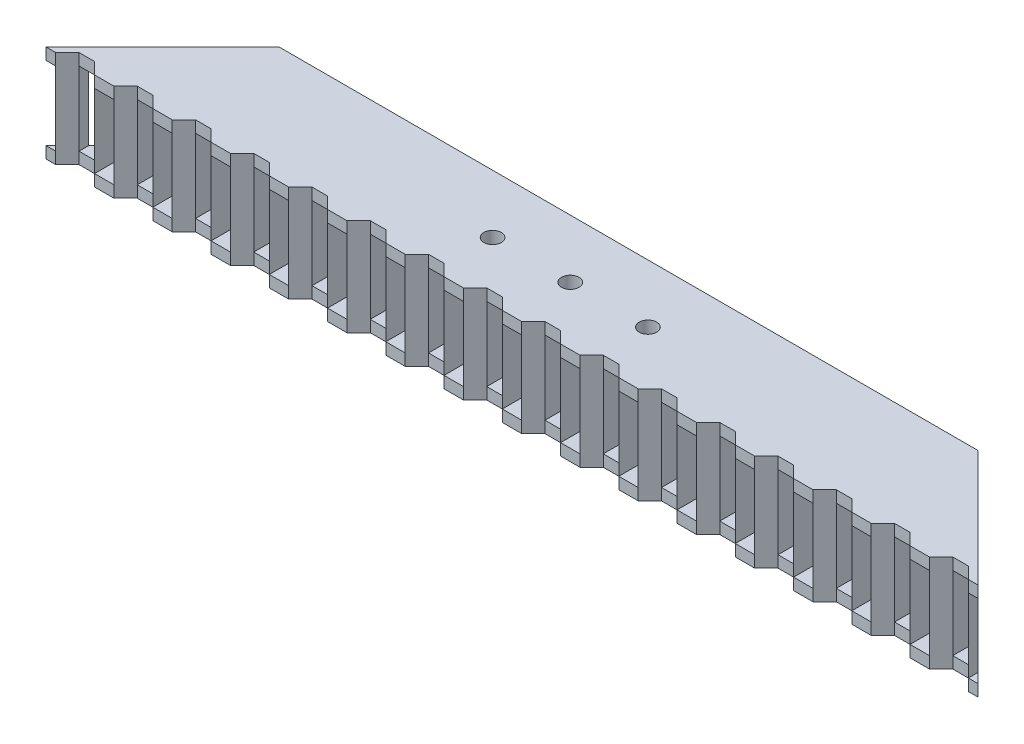
SolidWorks part; units mm, degrees
ref_plane "Front Plane" through (0, 0, 0) normal (0, 0, 1) x (1, 0, 0)
ref_plane "Top Plane" through (0, 0, 0) normal (0, 1, 0) x (1, 0, 0)
ref_plane "Right Plane" through (0, 0, 0) normal (1, 0, 0) x (0, 0, -1)
sketch "Sketch1" plane through (0, 0, 0) normal (0, 1, 0) x (1, 0, 0)
  line L0 (0, 0) -> (-120, 0)
  line L1 (0, 0) -> (120, 0)
  line L2 (120, 0) -> (90, 30)
  line L3 (90, 30) -> (-90, 30)
  line L4 (-90, 30) -> (-120, 0)
  line L5 (-105, 15) -> (0, 15) construction
  line L6 (0, 15) -> (0, 30) construction
  circle A0 centre (0, 15) radius 2.25
  circle A1 centre (-20, 15) radius 2.25
  circle A2 centre (20, 15) radius 2.25
  dimension "D6" = 4.5
  dimension "D1" = 45
  dimension "D2" = 45
  dimension "D3" = 30
  dimension "D4" = 120
  dimension "D5" = 120
  dimension "D7" = 20
  dimension "D8" = 20
extrude "Boss-Extrude1" add sketch "Sketch1" along normal blind 25
sketch "Sketch2" plane through (0, 25, 0) normal (0, 1, 0) x (1, 0, 0)
  line L0 (0, 0) -> (2.5, 0)
  line L1 (-120, 0) -> (120, 0) construction
  line L2 (2.5, 0) -> (5.5, 3)
  line L3 (5.5, 3) -> (9.5, 3)
  line L4 (9.5, 3) -> (12.5, 0)
  line L5 (0, 0) -> (-2.5, 0)
  line L6 (15, 0) -> (12.5, 0)
  line L7 (15, 0) -> (17.5, 0)
  line L8 (17.5, 0) -> (20.5, 3)
  line L9 (20.5, 3) -> (24.5, 3)
  line L10 (24.5, 3) -> (27.5, 0)
  line L11 (30, 0) -> (27.5, 0)
  line L12 (30, 0) -> (32.5, 0)
  line L13 (32.5, 0) -> (35.5, 3)
  line L14 (35.5, 3) -> (39.5, 3)
  line L15 (39.5, 3) -> (42.5, 0)
  line L16 (45, 0) -> (42.5, 0)
  line L17 (45, 0) -> (47.5, 0)
  line L18 (47.5, 0) -> (50.5, 3)
  line L19 (50.5, 3) -> (54.5, 3)
  line L20 (54.5, 3) -> (57.5, 0)
  line L21 (60, 0) -> (57.5, 0)
  line L22 (60, 0) -> (62.5, 0)
  line L23 (62.5, 0) -> (65.5, 3)
  line L24 (65.5, 3) -> (69.5, 3)
  line L25 (69.5, 3) -> (72.5, 0)
  line L26 (75, 0) -> (72.5, 0)
  line L27 (75, 0) -> (77.5, 0)
  line L28 (77.5, 0) -> (80.5, 3)
  line L29 (80.5, 3) -> (84.5, 3)
  line L30 (84.5, 3) -> (87.5, 0)
  line L31 (90, 0) -> (87.5, 0)
  line L32 (90, 0) -> (92.5, 0)
  line L33 (92.5, 0) -> (95.5, 3)
  line L34 (95.5, 3) -> (99.5, 3)
  line L35 (99.5, 3) -> (102.5, 0)
  line L36 (105, 0) -> (102.5, 0)
  line L37 (105, 0) -> (107.5, 0)
  line L38 (107.5, 0) -> (110.5, 3)
  line L39 (110.5, 3) -> (114.5, 3)
  line L40 (114.5, 3) -> (117.5, 0)
  line L41 (120, 0) -> (117.5, 0)
  line L42 (120, 0) -> (122.5, 0)
  line L43 (122.5, 0) -> (125.5, 3)
  line L44 (125.5, 3) -> (129.5, 3)
  line L45 (129.5, 3) -> (132.5, 0)
  line L46 (-15, 0) -> (-17.5, 0)
  line L47 (-15, 0) -> (-12.5, 0)
  line L48 (-12.5, 0) -> (-9.5, 3)
  line L49 (-9.5, 3) -> (-5.5, 3)
  line L50 (-5.5, 3) -> (-2.5, 0)
  line L51 (-30, 0) -> (-32.5, 0)
  line L52 (-30, 0) -> (-27.5, 0)
  line L53 (-27.5, 0) -> (-24.5, 3)
  line L54 (-24.5, 3) -> (-20.5, 3)
  line L55 (-20.5, 3) -> (-17.5, 0)
  line L56 (-45, 0) -> (-47.5, 0)
  line L57 (-45, 0) -> (-42.5, 0)
  line L58 (-42.5, 0) -> (-39.5, 3)
  line L59 (-39.5, 3) -> (-35.5, 3)
  line L60 (-35.5, 3) -> (-32.5, 0)
  line L61 (-60, 0) -> (-62.5, 0)
  line L62 (-60, 0) -> (-57.5, 0)
  line L63 (-57.5, 0) -> (-54.5, 3)
  line L64 (-54.5, 3) -> (-50.5, 3)
  line L65 (-50.5, 3) -> (-47.5, 0)
  line L66 (-75, 0) -> (-77.5, 0)
  line L67 (-75, 0) -> (-72.5, 0)
  line L68 (-72.5, 0) -> (-69.5, 3)
  line L69 (-69.5, 3) -> (-65.5, 3)
  line L70 (-65.5, 3) -> (-62.5, 0)
  line L71 (-90, 0) -> (-92.5, 0)
  line L72 (-90, 0) -> (-87.5, 0)
  line L73 (-87.5, 0) -> (-84.5, 3)
  line L74 (-84.5, 3) -> (-80.5, 3)
  line L75 (-80.5, 3) -> (-77.5, 0)
  line L76 (-105, 0) -> (-107.5, 0)
  line L77 (-105, 0) -> (-102.5, 0)
  line L78 (-102.5, 0) -> (-99.5, 3)
  line L79 (-99.5, 3) -> (-95.5, 3)
  line L80 (-95.5, 3) -> (-92.5, 0)
  line L81 (-120, 0) -> (-122.5, 0)
  line L82 (-120, 0) -> (-117.5, 0)
  line L83 (-117.5, 0) -> (-114.5, 3)
  line L84 (-114.5, 3) -> (-110.5, 3)
  line L85 (-110.5, 3) -> (-107.5, 0)
  line L86 (-122.5, 0) -> (-122.5, -12)
  line L87 (-122.5, -12) -> (132.5, -12)
  line L88 (132.5, -12) -> (132.5, 0)
  line M6 (-120, 0) -> (120, 0)
  dimension "D1" = 2.5
  dimension "D2" = 3
  dimension "D3" = 10
  dimension "D4" = 2.5
  dimension "D5" = 9
  dimension "D6" = 9
extrude "Cut-Extrude1" cut sketch "Sketch2" against normal blind 25 contours L40 L39 L38 M6 | L35 L34 L33 M6 | L30 L29 L28 M6 | L25 L24 L23 M6 | L20 L19 L18 M6 | L15 L14 L13 M6 | L10 L9 L8 M6 | L4 L3 L2 M6 | L50 L49 L48 M6 | L55 L54 L53 M6 | L60 L59 L58 M6 | L65 L64 L63 M6 | L70 L69 L68 M6 | L75 L74 L73 M6 | L80 L79 L78 M6 | L85 L84 L83 M6
sketch "Sketch3" plane through (0, 0, 0) normal (0, 0, 1) x (1, 0, 0)
  line L0 (-107.5, 0) -> (-107.5, 25) construction
  line L1 (-107.5, 22) -> (-102.5, 22)
  line L2 (-107.5, 22) -> (-107.5, 3)
  line L3 (-107.5, 3) -> (-102.5, 3)
  line L4 (-102.5, 22) -> (-102.5, 3)
  line L5 (-102.5, 0) -> (-102.5, 25) construction
  line L6 (-107.5, 25) -> (-102.5, 25) construction
  line L7 (-107.5, 0) -> (-102.5, 0) construction
  line L8 (-92.5, 3) -> (-87.5, 3)
  line L9 (-92.5, 22) -> (-92.5, 3)
  line L10 (-87.5, 22) -> (-87.5, 3)
  line L11 (-92.5, 22) -> (-87.5, 22)
  line L12 (-77.5, 3) -> (-72.5, 3)
  line L13 (-77.5, 22) -> (-77.5, 3)
  line L14 (-72.5, 22) -> (-72.5, 3)
  line L15 (-77.5, 22) -> (-72.5, 22)
  line L16 (-62.5, 3) -> (-57.5, 3)
  line L17 (-62.5, 22) -> (-62.5, 3)
  line L18 (-57.5, 22) -> (-57.5, 3)
  line L19 (-62.5, 22) -> (-57.5, 22)
  line L20 (-47.5, 3) -> (-42.5, 3)
  line L21 (-47.5, 22) -> (-47.5, 3)
  line L22 (-42.5, 22) -> (-42.5, 3)
  line L23 (-47.5, 22) -> (-42.5, 22)
  line L24 (-32.5, 3) -> (-27.5, 3)
  line L25 (-32.5, 22) -> (-32.5, 3)
  line L26 (-27.5, 22) -> (-27.5, 3)
  line L27 (-32.5, 22) -> (-27.5, 22)
  line L28 (-17.5, 3) -> (-12.5, 3)
  line L29 (-17.5, 22) -> (-17.5, 3)
  line L30 (-12.5, 22) -> (-12.5, 3)
  line L31 (-17.5, 22) -> (-12.5, 22)
  line L32 (-2.5, 3) -> (2.5, 3)
  line L33 (-2.5, 22) -> (-2.5, 3)
  line L34 (2.5, 22) -> (2.5, 3)
  line L35 (-2.5, 22) -> (2.5, 22)
  line L36 (12.5, 3) -> (17.5, 3)
  line L37 (12.5, 22) -> (12.5, 3)
  line L38 (17.5, 22) -> (17.5, 3)
  line L39 (12.5, 22) -> (17.5, 22)
  line L40 (27.5, 3) -> (32.5, 3)
  line L41 (27.5, 22) -> (27.5, 3)
  line L42 (32.5, 22) -> (32.5, 3)
  line L43 (27.5, 22) -> (32.5, 22)
  line L44 (42.5, 3) -> (47.5, 3)
  line L45 (42.5, 22) -> (42.5, 3)
  line L46 (47.5, 22) -> (47.5, 3)
  line L47 (42.5, 22) -> (47.5, 22)
  line L48 (57.5, 3) -> (62.5, 3)
  line L49 (57.5, 22) -> (57.5, 3)
  line L50 (62.5, 22) -> (62.5, 3)
  line L51 (57.5, 22) -> (62.5, 22)
  line L52 (72.5, 3) -> (77.5, 3)
  line L53 (72.5, 22) -> (72.5, 3)
  line L54 (77.5, 22) -> (77.5, 3)
  line L55 (72.5, 22) -> (77.5, 22)
  line L56 (87.5, 3) -> (92.5, 3)
  line L57 (87.5, 22) -> (87.5, 3)
  line L58 (92.5, 22) -> (92.5, 3)
  line L59 (87.5, 22) -> (92.5, 22)
  line L60 (102.5, 3) -> (107.5, 3)
  line L61 (102.5, 22) -> (102.5, 3)
  line L62 (107.5, 22) -> (107.5, 3)
  line L63 (102.5, 22) -> (107.5, 22)
  line L64 (117.5, 3) -> (122.5, 3)
  line L65 (117.5, 22) -> (117.5, 3)
  line L66 (122.5, 22) -> (122.5, 3)
  line L67 (117.5, 22) -> (122.5, 22)
  line L68 (-117.5, 0) -> (-117.5, 25) construction
  line L69 (-117.5, 22) -> (-128.3199, 22)
  line L70 (-117.5, 22) -> (-117.5, 3)
  line L71 (-117.5, 3) -> (-128.3199, 3)
  line L72 (-128.3199, 22) -> (-128.3199, 3)
  line L73 (-120, 25) -> (-117.5, 25) construction
  line L74 (-120, 0) -> (-117.5, 0) construction
  point P80 (-118.75, 25)
  point P83 (-118.75, 0)
  dimension "D1" = 3
  dimension "D2" = 3
  dimension "D4" = 3
  dimension "D5" = 3
  dimension "D3" = 16
extrude "Cut-Extrude2" cut sketch "Sketch3" against normal blind 51
sketch "Sketch4" plane through (0, 0, -3) normal (0, 0, 1) x (1, 0, 0)
  line L0 (-114.5, 0) -> (-114.5, 25) construction
  line L1 (-114.5, 22) -> (-110.5, 22)
  line L2 (-114.5, 22) -> (-114.5, 3)
  line L3 (-114.5, 3) -> (-110.5, 3)
  line L4 (-110.5, 22) -> (-110.5, 3)
  line L5 (-110.5, 0) -> (-110.5, 25) construction
  line L6 (-114.5, 25) -> (-110.5, 25) construction
  line L7 (-114.5, 0) -> (-110.5, 0) construction
  line L8 (-99.5, 3) -> (-95.5, 3)
  line L9 (-99.5, 22) -> (-99.5, 3)
  line L10 (-95.5, 22) -> (-95.5, 3)
  line L11 (-99.5, 22) -> (-95.5, 22)
  line L12 (-84.5, 3) -> (-80.5, 3)
  line L13 (-84.5, 22) -> (-84.5, 3)
  line L14 (-80.5, 22) -> (-80.5, 3)
  line L15 (-84.5, 22) -> (-80.5, 22)
  line L16 (-69.5, 3) -> (-65.5, 3)
  line L17 (-69.5, 22) -> (-69.5, 3)
  line L18 (-65.5, 22) -> (-65.5, 3)
  line L19 (-69.5, 22) -> (-65.5, 22)
  line L20 (-54.5, 3) -> (-50.5, 3)
  line L21 (-54.5, 22) -> (-54.5, 3)
  line L22 (-50.5, 22) -> (-50.5, 3)
  line L23 (-54.5, 22) -> (-50.5, 22)
  line L24 (-39.5, 3) -> (-35.5, 3)
  line L25 (-39.5, 22) -> (-39.5, 3)
  line L26 (-35.5, 22) -> (-35.5, 3)
  line L27 (-39.5, 22) -> (-35.5, 22)
  line L28 (-24.5, 3) -> (-20.5, 3)
  line L29 (-24.5, 22) -> (-24.5, 3)
  line L30 (-20.5, 22) -> (-20.5, 3)
  line L31 (-24.5, 22) -> (-20.5, 22)
  line L32 (-9.5, 3) -> (-5.5, 3)
  line L33 (-9.5, 22) -> (-9.5, 3)
  line L34 (-5.5, 22) -> (-5.5, 3)
  line L35 (-9.5, 22) -> (-5.5, 22)
  line L36 (5.5, 3) -> (9.5, 3)
  line L37 (5.5, 22) -> (5.5, 3)
  line L38 (9.5, 22) -> (9.5, 3)
  line L39 (5.5, 22) -> (9.5, 22)
  line L40 (20.5, 3) -> (24.5, 3)
  line L41 (20.5, 22) -> (20.5, 3)
  line L42 (24.5, 22) -> (24.5, 3)
  line L43 (20.5, 22) -> (24.5, 22)
  line L44 (35.5, 3) -> (39.5, 3)
  line L45 (35.5, 22) -> (35.5, 3)
  line L46 (39.5, 22) -> (39.5, 3)
  line L47 (35.5, 22) -> (39.5, 22)
  line L48 (50.5, 3) -> (54.5, 3)
  line L49 (50.5, 22) -> (50.5, 3)
  line L50 (54.5, 22) -> (54.5, 3)
  line L51 (50.5, 22) -> (54.5, 22)
  line L52 (65.5, 3) -> (69.5, 3)
  line L53 (65.5, 22) -> (65.5, 3)
  line L54 (69.5, 22) -> (69.5, 3)
  line L55 (65.5, 22) -> (69.5, 22)
  line L56 (80.5, 3) -> (84.5, 3)
  line L57 (80.5, 22) -> (80.5, 3)
  line L58 (84.5, 22) -> (84.5, 3)
  line L59 (80.5, 22) -> (84.5, 22)
  line L60 (95.5, 3) -> (99.5, 3)
  line L61 (95.5, 22) -> (95.5, 3)
  line L62 (99.5, 22) -> (99.5, 3)
  line L63 (95.5, 22) -> (99.5, 22)
  line L64 (110.5, 3) -> (114.5, 3)
  line L65 (110.5, 22) -> (110.5, 3)
  line L66 (114.5, 22) -> (114.5, 3)
  line L67 (110.5, 22) -> (114.5, 22)
  dimension "D1" = 3
  dimension "D2" = 3
  dimension "D3" = 16
extrude "Cut-Extrude3" cut sketch "Sketch4" against normal blind 51
sketch "Sketch5" plane through (0, 25, 0) normal (0, 1, 0) x (1, 0, 0)
  circle A0 centre (-20, 15) radius 2.25
  circle A1 centre (-20, 15) radius 7
  circle A2 centre (0, 15) radius 2.25
  circle A3 centre (0, 15) radius 7
  circle A4 centre (20, 15) radius 2.25
  circle A5 centre (20, 15) radius 7
  dimension "D1" = 14
extrude "Boss-Extrude4" add sketch "Sketch5" against normal blind 24
